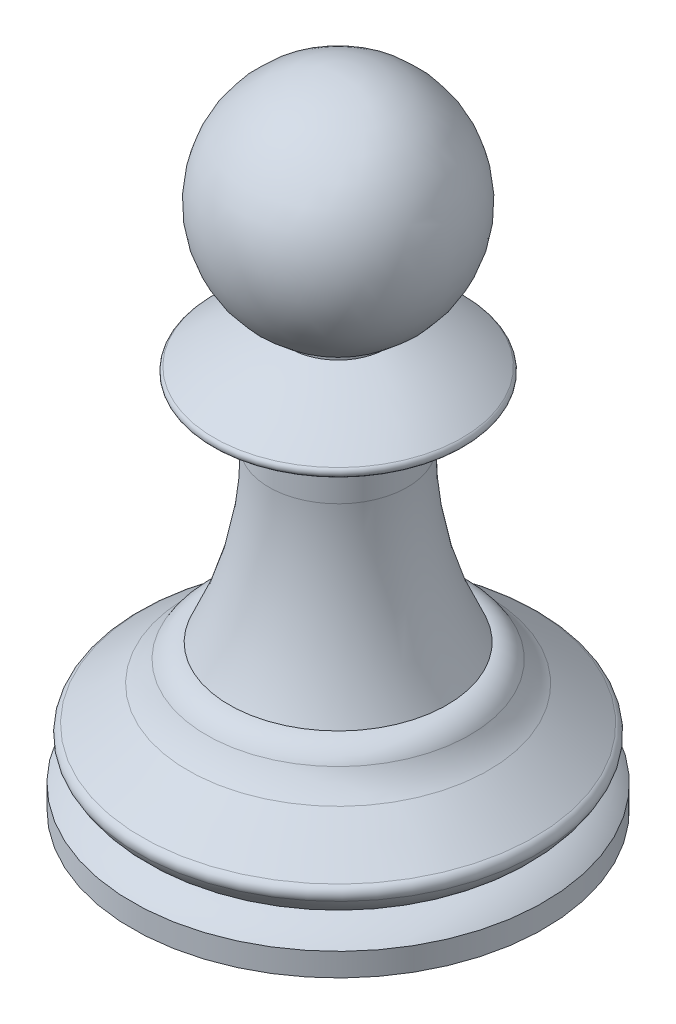
SolidWorks part; units mm, degrees
material "CA"
ref_plane "Front Plane" through (0, 0, 0) normal (0, 0, 1) x (1, 0, 0)
ref_plane "Top Plane" through (0, 0, 0) normal (0, 1, 0) x (1, 0, 0)
ref_plane "Right Plane" through (0, 0, 0) normal (1, 0, 0) x (0, 0, -1)
sketch "Sketch2" plane through (0, 0, 0) normal (0, 0, 1) x (1, 0, 0)
  line L0 (55.874, 209.0199) -> (133.37, 209.0199) construction
  line L1 (0, 0) -> (-11.9699, 0)
  line L2 (-11.9699, 0) -> (-11.9699, 1.3403)
  line L3 (-11.4125, 4.33) -> (-8.7371, 6.3525)
  line L4 (0, 0) -> (0, 37.0268)
  line L5 (-2.7782, 24.8454) -> (-2.7782, 24.5981)
  line L6 (-4.0213, 21.2082) -> (-4.0213, 18.2446)
  arc A0 (-11.9699, 1.3403) -> (-10.4045, 2.3145) centre (-8.6286, -2.2837) cw
  arc A1 (-10.4045, 2.3145) -> (-11.6321, 3.6132) centre (-8.6643, 5.189) cw
  arc A2 (-11.6321, 3.6132) -> (-11.4125, 4.33) centre (-11.1638, 3.8618) cw
  arc A3 (-8.7371, 6.3525) -> (-7.652, 7.5856) centre (-11.2077, 9.6206) ccw
  arc A4 (-7.652, 7.5856) -> (-6.3301, 8.4438) centre (-6.1569, 6.7299) cw
  arc A5 (0, 37.0268) -> (-2.7782, 24.8454) centre (0, 30.6193) ccw
  arc A6 (-2.7782, 24.5981) -> (-7.2058, 22.32) centre (3.3248, 7.2947) ccw
  arc A7 (-7.2058, 22.32) -> (-7.1157, 21.7998) centre (-7.0383, 22.0811) ccw
  arc A8 (-7.1157, 21.7998) -> (-4.0213, 21.2082) centre (-1.8604, 40.8973) ccw
  arc A9 (-4.0213, 18.2446) -> (-6.3301, 8.4438) centre (-25.9778, 18.2446) cw
revolve "Revolve1" add sketch "Sketch2" angle 360 about L4
